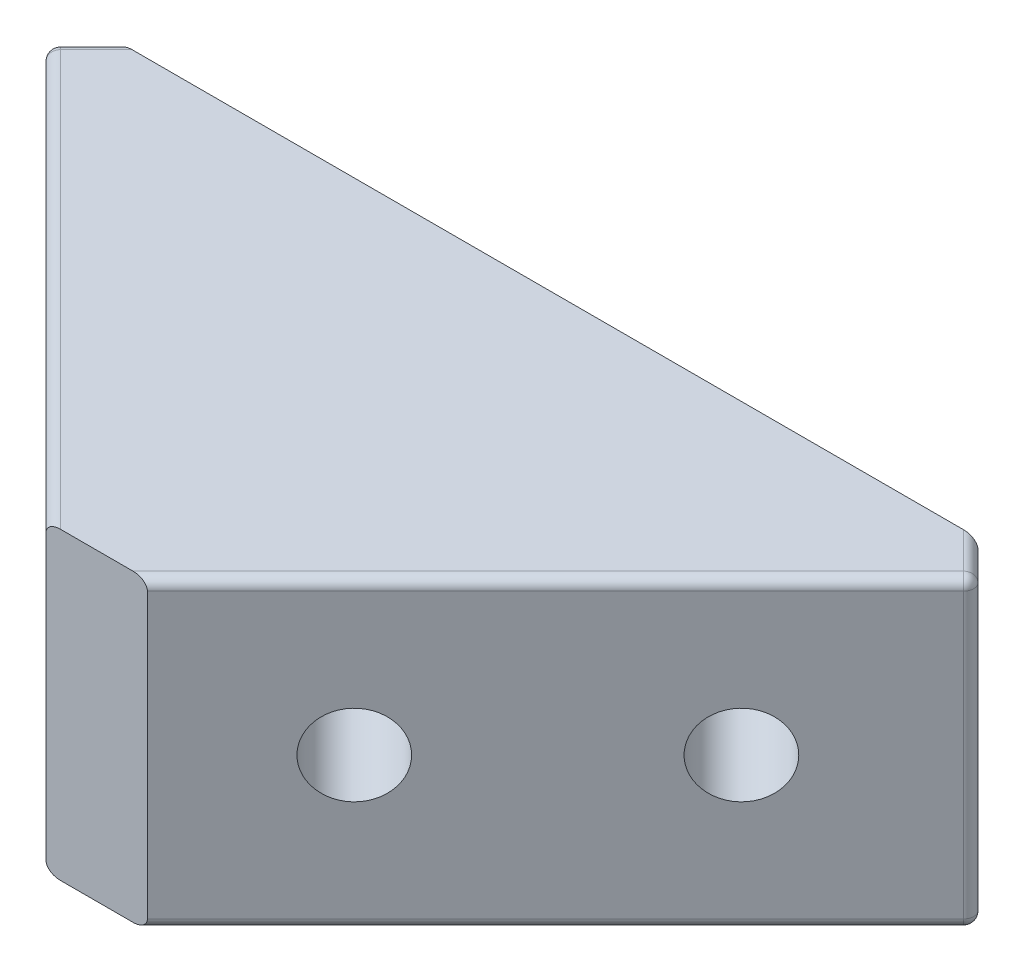
SolidWorks part; units mm, degrees
ref_plane "Front Plane" through (0, 0, 0) normal (0, 0, 1) x (1, 0, 0)
ref_plane "Top Plane" through (0, 0, 0) normal (0, 1, 0) x (1, 0, 0)
ref_plane "Right Plane" through (0, 0, 0) normal (1, 0, 0) x (0, 0, -1)
sketch "Sketch1" plane through (0, 0, 0) normal (0, 1, 0) x (1, 0, 0)
  line L0 (-24.7487, 0) -> (24.7487, 0)
  line L1 (24.7487, 0) -> (0, -24.7487)
  line L2 (0, -24.7487) -> (-24.7487, 0)
  point P4 (0, -0.0285)
  point P5 (0, -0.0322)
  point P7 (0, 0)
  point P8 (-20.7613, 4.3554)
  dimension "D1" = 35
extrude "Boss-Extrude1" add sketch "Sketch1" along normal blind 15
sketch "Sketch3" plane through (0, 0, 0) normal (0, -1, 0) x (1, 0, 0)
  line L0 (-2.5, 22.2487) -> (0, 24.7487)
  line L1 (0, 24.7487) -> (2.5, 22.2487)
  line L2 (2.5, 22.2487) -> (-2.5, 22.2487)
  line L3 (0, 24.7487) -> (-24.7487, 0)
  line L4 (-24.7487, 0) -> (24.7487, 0)
  line L5 (24.7487, 0) -> (0, 24.7487)
  line L6 (0, 24.7487) -> (-24.7487, 0) construction
  line L7 (-24.7487, 0) -> (24.7487, 0) construction
  line L8 (24.7487, 0) -> (0, 24.7487) construction
  line L9 (-24.7487, 0) -> (0, 24.7487) construction
  line L10 (-24.7487, 0) -> (-22.981, 1.7678)
  line L11 (-22.981, 1.7678) -> (-21.2132, 0)
  line L12 (-21.2132, 0) -> (-24.7487, 0)
  line L14 (24.7487, 0) -> (21.2132, 0)
  line L15 (21.2132, 0) -> (22.981, 1.7678)
  line L16 (22.981, 1.7678) -> (24.7487, 0)
  point P0 (-21.2132, 0)
  dimension "D2" = 2.5
  dimension "D3" = 2.5
  dimension "D4" = 2.5
  dimension "D1" = 0
sketch "Sketch9" plane through (12.3744, 0, 12.3744) normal (0.7071, 0, 0.7071) x (0.7071, 0, -0.7071)
  line L0 (-17.5, 15) -> (0, 0) construction
  line L1 (0, 0) -> (17.5, 15) construction
  line L2 (-17.5, 0) -> (0, 15) construction
  line L3 (0, 15) -> (17.5, 0) construction
  line L4 (-17.5, 0) -> (17.5, 0)
  line L5 (17.5, 0) -> (17.5, 15)
  line L6 (17.5, 15) -> (-17.5, 15)
  line L7 (-17.5, 15) -> (-17.5, 0)
  line L8 (-17.5, 0) -> (17.5, 0) construction
  line L9 (17.5, 0) -> (17.5, 15) construction
  line L10 (17.5, 15) -> (-17.5, 15) construction
  line L11 (-17.5, 15) -> (-17.5, 0) construction
  circle A0 centre (-6.75, 7.5) radius 2
  circle A1 centre (6.75, 7.5) radius 2
  point P10 (0, 0)
  point P11 (-1.5996, 7.5)
  point P12 (3.9315, 7.2408)
  point P13 (-8.75, 7.5)
  point P14 (0, 0)
  point P15 (5.75, 7.5)
  point P16 (-5.75, 7.5)
  point P17 (0, 0)
  point P18 (0, 0)
  point P19 (0, 0)
  point P20 (-5.9268, 8.2664)
  point P21 (-17.5, 7.5)
  point P22 (0, 0)
  point P23 (8.75, 7.5)
  dimension "D2" = 4
  dimension "D1" = 0
sketch "Sketch10" plane through (-12.3744, 0, 12.3744) normal (-0.7071, 0, 0.7071) x (0.7071, 0, 0.7071)
  line L0 (-17.5, 15) -> (0, 0) construction
  line L1 (0, 0) -> (17.5, 15) construction
  line L2 (-17.5, 0) -> (0, 15) construction
  line L3 (0, 15) -> (17.5, 0) construction
  line L4 (-17.5, 0) -> (17.5, 0)
  line L5 (17.5, 0) -> (17.5, 15)
  line L6 (17.5, 15) -> (-17.5, 15)
  line L7 (-17.5, 15) -> (-17.5, 0)
  line L8 (-17.5, 0) -> (17.5, 0) construction
  line L9 (17.5, 0) -> (17.5, 15) construction
  line L10 (17.5, 15) -> (-17.5, 15) construction
  line L11 (-17.5, 15) -> (-17.5, 0) construction
  circle A0 centre (-6.75, 7.5) radius 2
  circle A1 centre (6.75, 7.5) radius 2
  point P10 (-3.6155, 7.5)
  point P11 (4.0434, 7.5)
  point P12 (0, 0)
  point P13 (0, 0)
  point P14 (8.75, 7.5)
  point P15 (-8.75, 7.5)
  point P16 (17.5, 7.5)
  dimension "D2" = 4
  dimension "D1" = 0
extrude "Cut-Extrude5" cut sketch "Sketch9" against normal up to surface (22.25 mm away)
extrude "Cut-Extrude6" cut sketch "Sketch10" against normal up to surface (12.75 mm away)
extrude "Cut-Extrude7" cut sketch "Sketch3" against normal up to next
fillet "Fillet1" radius 0.5 10 edges at (-12.7405, 15, 12.0083) (-22.0971, 15, 0.8839) (-12.7405, 0, 12.0083) (12.7405, 0, 12.0083) (12.7405, 15, 12.0083) (22.0971, 15, 0.8839) (-22.0971, 0, 0.8839) (22.0971, 0, 0.8839) (22.981, 7.5, 1.7678) (-22.981, 7.5, 1.7678)
ref_plane "Plane1" through (-8.1317, 0, 8.1317) normal (-0.7071, 0, 0.7071) x (0.7071, 0, 0.7071)
sketch "Sketch11" plane through (-8.1317, 0, 8.1317) normal (-0.7071, 0, 0.7071) x (0.7071, 0, 0.7071)
  circle A0 centre (6.75, 7.5) radius 2 construction
  circle A1 centre (-6.75, 7.5) radius 2 construction
  circle A2 centre (6.75, 7.5) radius 2 construction
  circle A3 centre (-6.75, 7.5) radius 2 construction
  circle A4 centre (-6.75, 7.5) radius 3.5
  circle A5 centre (6.75, 7.5) radius 3.5
  dimension "D1" = 7
extrude "Cut-Extrude8" cut sketch "Sketch11" against normal up to surface (8.25 mm away)
ref_plane "Plane2" through (8.1317, 0, 8.1317) normal (0.7071, 0, 0.7071) x (0.7071, 0, -0.7071)
sketch "Sketch12" plane through (8.1317, 0, 8.1317) normal (0.7071, 0, 0.7071) x (0.7071, 0, -0.7071)
  circle A0 centre (-6.75, 7.5) radius 2 construction
  circle A1 centre (6.75, 7.5) radius 2 construction
  circle A2 centre (-6.75, 7.5) radius 2 construction
  circle A3 centre (6.75, 7.5) radius 2 construction
  circle A4 centre (6.75, 7.5) radius 3.5
  circle A5 centre (-6.75, 7.5) radius 3.5
  dimension "D1" = 7
extrude "Cut-Extrude9" cut sketch "Sketch12" against normal up to surface (1.25 mm away)
